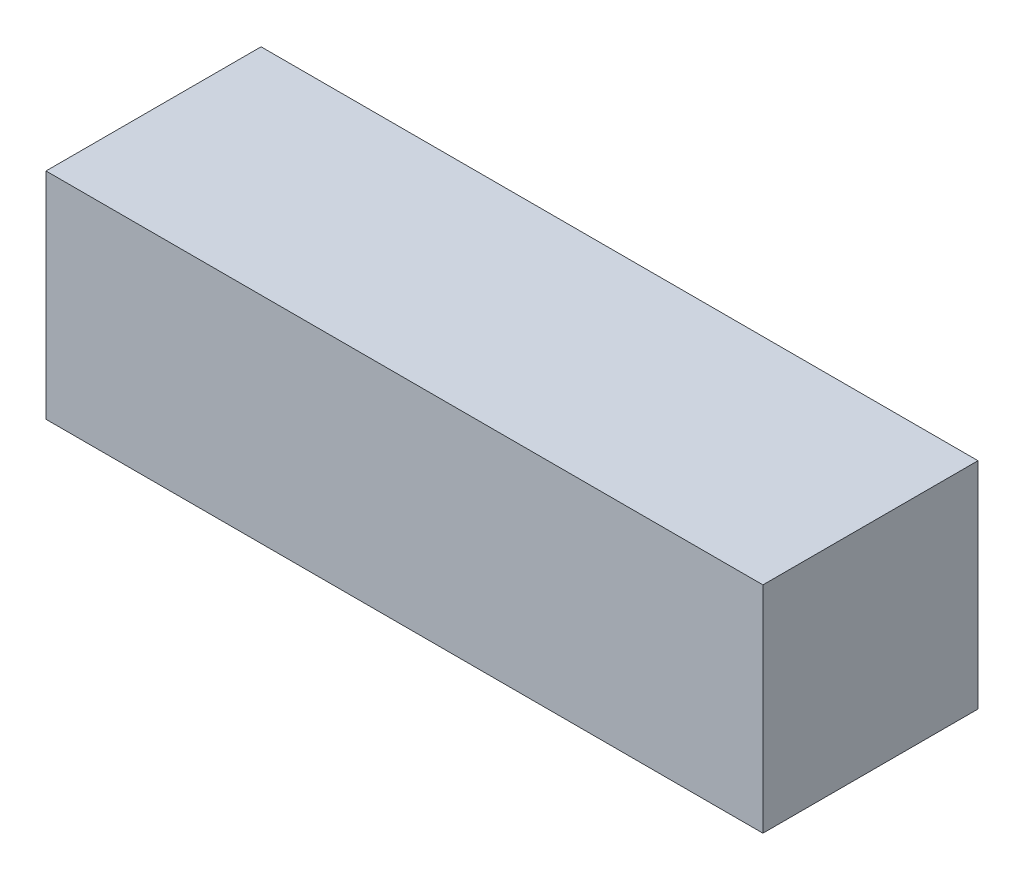
SolidWorks part; units mm, degrees
ref_plane "前视基准面" through (0, 0, 0) normal (0, 0, 1) x (1, 0, 0)
ref_plane "上视基准面" through (0, 0, 0) normal (0, 1, 0) x (1, 0, 0)
ref_plane "右视基准面" through (0, 0, 0) normal (1, 0, 0) x (0, 0, -1)
sketch "草图2" plane through (0, 0, 0) normal (1, 0, 0) x (0, 0, -1)
  line L1 (-3, 3) -> (3, 3)
  line L2 (-3, 3) -> (-3, -3)
  line L3 (-3, -3) -> (3, -3)
  line L4 (3, 3) -> (3, -3)
  line L5 (-3, 3) -> (3, -3) construction
  line L6 (-3, -3) -> (3, 3) construction
  point P0 (0, 0)
  dimension "D1" = 6
  dimension "D2" = 6
extrude "凸台-拉伸1" add sketch "草图2" along normal blind 20
